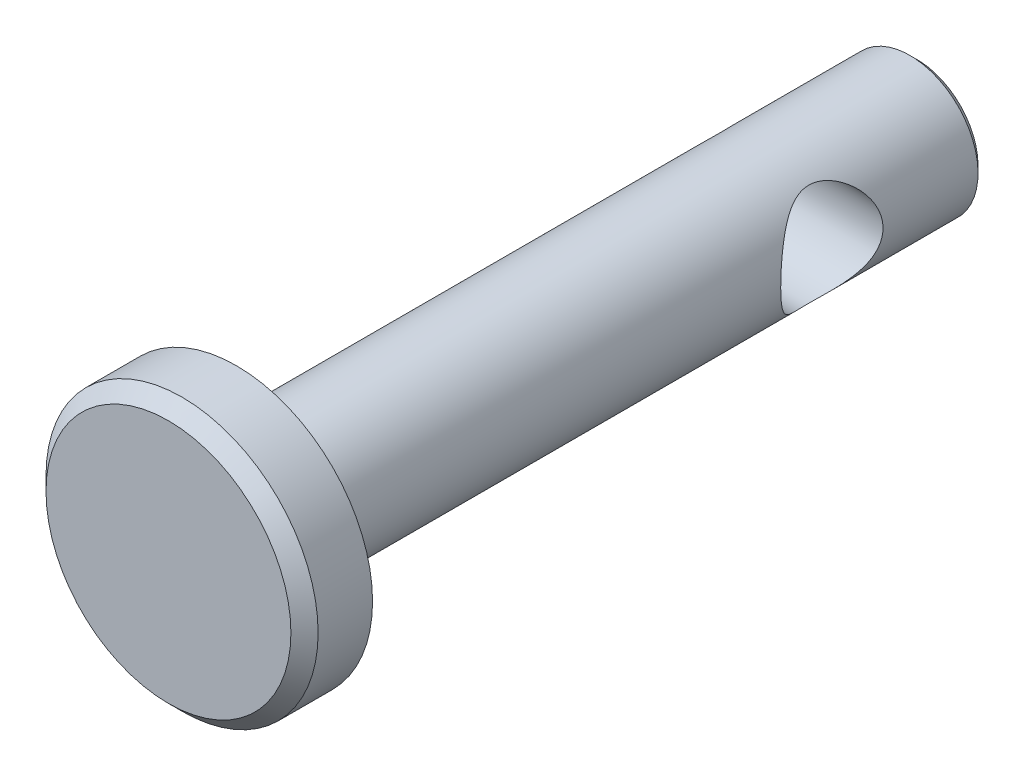
SolidWorks part; units mm, degrees
ref_plane "Front" through (0, 0, 0) normal (0, 0, 1) x (1, 0, 0)
ref_plane "Top" through (0, 0, 0) normal (0, 1, 0) x (1, 0, 0)
ref_plane "Right" through (0, 0, 0) normal (1, 0, 0) x (0, 0, -1)
sketch "Sketch1" plane through (0, 0, 0) normal (1, 0, 0) x (0, 0, -1)
  line L0 (0, 0) -> (15.875, 0) construction
  line L1 (0, 0) -> (-1.5875, 0) construction
  line L2 (15.875, 1.5875) -> (15.875, -1.5875) construction
  line L3 (0, 3.175) -> (0, -3.175) construction
  line L4 (11.1125, 0) -> (13.5001, 0) construction
  line L5 (15.875, 1.5875) -> (0, 1.5875) construction
  line L6 (15.875, -1.5875) -> (0, -1.5875) construction
  line L7 (11.1125, 0) -> (11.1125, -1.5875) construction
  point P10 (15.875, 0)
  point P12 (0, 0)
  point P13 (12.3063, 0)
  point P14 (-1.5875, 3.175)
  point P17 (12.3063, 0)
  point P18 (11.1125, 0)
  point P21 (-1.5875, -3.175)
  dimension "Length" = 15.875
  dimension "Diameter" = 3.175
  dimension "Through Hole Diameter" = 2.3876
  dimension "Usable Length" = 11.1125
  dimension "Head Height" = 1.5875
  dimension "Head Diameter" = 6.35
sketch "Sketch4" plane through (0, 0, 0) normal (1, 0, 0) x (0, 0, -1)
  line L0 (-1.5875, 0) -> (15.875, 0)
  line L1 (15.875, 0) -> (15.875, 1.5875)
  line L2 (15.875, 1.5875) -> (0, 1.5875)
  line L3 (0, 3.175) -> (0, -3.175) construction
  line L4 (0, 1.5875) -> (0, 3.175)
  line L5 (0, 3.175) -> (-1.5875, 3.175)
  line L6 (-1.5875, 3.175) -> (-1.5875, 0)
revolve "Revolve1" add sketch "Sketch4" angle 360 about L0
sketch "Sketch2" plane through (0, 0, 6.35) normal (-1, 0, 0) x (0, 0, 1)
  circle A0 centre (-18.6563, 0) radius 1.1938
extrude "Cut-Extrude1" cut sketch "Sketch2" against normal through all and the other way through all
chamfer "Chamfer1" distance 0.3175 angle 45 1 edges at (0, -3.175, 1.5875)
chamfer "Chamfer2" distance 0.1588 angle 45 1 edges at (0, -1.5875, -15.875)
equation "\"D1@Chamfer1\" = \"Head Height@Sketch1\" * .2"
equation "\"D1@Chamfer2\" = \"Diameter@Sketch1\" * .05"
